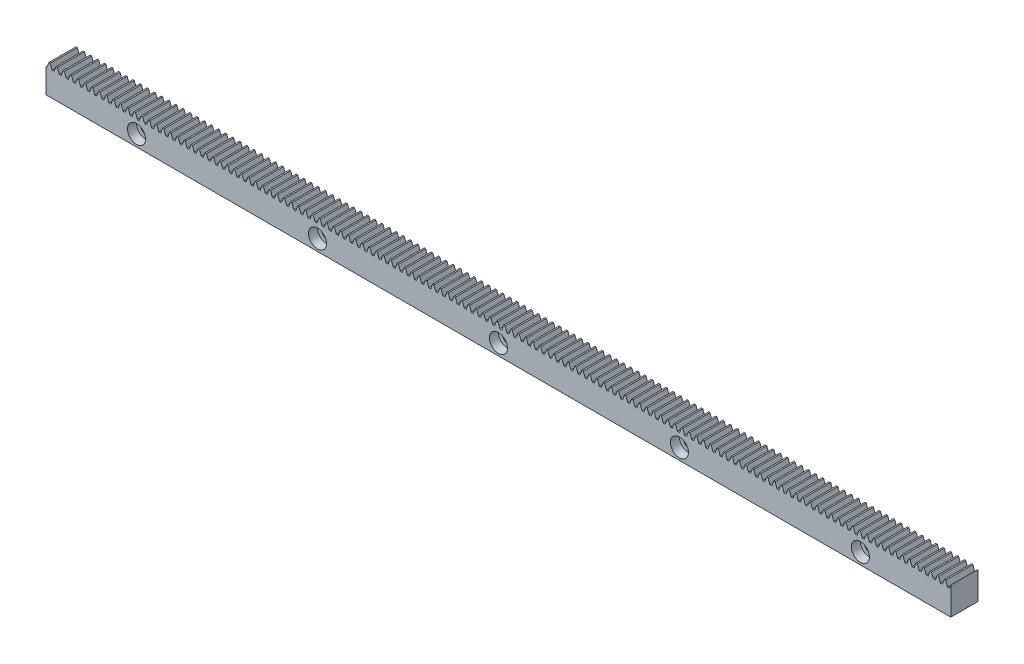
SolidWorks part; units mm, degrees
extrude "Blank" add sketch "BlankSke" against normal blind 12
sketch "BlankSke" plane through (0, 0, 0) normal (0, 0, 1) x (1, 0, 0)
  line L1 (0, 0) -> (400, 0)
  line L2 (0, 0) -> (0, 13)
  line L3 (0, 13) -> (400, 13)
  line L4 (400, 0) -> (400, 13)
  dimension "Length" = 400
  dimension "Blank_height" = 13
ref_plane "Plane1" through (0, 0, 0) normal (0, 0, 1) x (1, 0, 0)
ref_plane "Plane2" through (0, 0, 0) normal (0, 1, 0) x (1, 0, 0)
ref_plane "Plane3" through (0, 0, 0) normal (1, 0, 0) x (0, 0, -1)
sketch "HoldingSke" plane through (0, 0, 0) normal (0, 1, 0) x (1, 0, 0)
  line L0 (0, 0) -> (-0.766, -0.6428)
  line L1 (-15, 0) -> (100, 0) construction
  line L2 (0, 0) -> (-2.1039, 2.3779)
  line L3 (0, 0) -> (-11.863, 4.5341)
  line L4 (0, 0) -> (-5.4348, 6.7114)
  line L5 (0, 0) -> (-23.7986, -8.8762)
  line L6 (0, 0) -> (-10.5278, -7.1032)
  line L9 (-71.009, 38.7566) -> (304.8681, 175.5647)
  line L10 (-76.2, 3.3779) -> (-64.2, 3.3779)
  line L11 (0, 0) -> (-6.35, 0)
  line L12 (-76.2, 101.6) -> (-76.162, 101.6)
  line L13 (24.9733, 27.94) -> (52.9518, 28.4284)
  line L14 (24.9733, 27.94) -> (24.9743, 27.94)
  line L15 (24.9733, 27.94) -> (100.4006, 29.5858)
  circle A0 centre (0, 0) radius 19.05
  circle A1 centre (0, 0) radius 6
  circle A2 centre (0, 0) radius 12.7
  dimension "MPH" = 12
  dimension "Diameter" = 38.1
  dimension "Num_teeth" = 129
  dimension "Pitch" = 1
  dimension "Show_teeth" = 500
  dimension "Thickness" = 12.7
  dimension "Ap" = 20
  dimension "Pitch_height" = 12
  dimension "Width" = 6.35
  dimension "Backlash" = 0.038
  dimension "Addendum_fac" = 1
  dimension "Dedendum_fac" = 1.25
  dimension "Clearance_fac" = 0.25
  dimension "Dedendum_add" = 0.001
  dimension "Length" = 400
  dimension "Module" = 1
sketch "TooCutSkeIll" plane through (0, 0, 0) normal (0, 0, 1) x (1, 0, 0)
  line L0 (-1.2538, 12.9737) -> (-0.5045, 10.9152)
  line L1 (-0.2687, 10.75) -> (0.2687, 10.75)
  line L2 (0.5045, 10.9152) -> (1.2538, 12.9737)
  line L3 (400, 13) -> (0, 13) construction
  line L4 (0, 0) -> (0, 64.897) construction
  line L5 (-13.208, 12) -> (12.954, 12) construction
  line L6 (0, 0) -> (400, 0) construction
  line L7 (0.8994, 12) -> (0.8994, 48.7463) construction
  line L8 (-0.8994, 12) -> (-0.8994, 48.7463) construction
  line L9 (1.2914, 13) -> (1.2914, 13.0254)
  line L10 (-1.2914, 13) -> (-1.2914, 13.0254)
  line L11 (-1.2914, 13.0254) -> (1.2914, 13.0254)
  arc A0 (0.2687, 10.75) -> (0.5045, 10.9152) centre (0.2687, 11.001) ccw
  arc A1 (-0.5045, 10.9152) -> (-0.2687, 10.75) centre (-0.2687, 11.001) ccw
  arc A2 (1.2914, 13) -> (1.2538, 12.9737) centre (1.2914, 12.96) ccw
  arc A3 (-1.2538, 12.9737) -> (-1.2914, 13) centre (-1.2914, 12.96) ccw
  dimension "Pitch_height" = 12
  dimension "Addendum_plus" = 1.0254
  dimension "Pressure_angle" = 20
  dimension "Gap_width" = 1.7988
  dimension "Dedendum" = 1.25
extrude "ToothCutIll" [suppressed] cut sketch "TooCutSkeIll" against normal through all
sketch "TooCutSkeSim" plane through (0, 0, 0) normal (0, 0, 1) x (1, 0, 0)
  line L0 (0.4444, 10.75) -> (-0.4444, 10.75)
  line L1 (1.2726, 13.0254) -> (0.4444, 10.75)
  line L2 (0, 17.4625) -> (0, 53.467) construction
  line L3 (1.2726, 13.0254) -> (-1.2726, 13.0254)
  line L6 (-1.2726, 13.0254) -> (-0.4444, 10.75)
  line L9 (-0.8994, 12) -> (0.8994, 12) construction
  line L10 (0, 0) -> (400, 0) construction
  line L11 (0.8994, 12) -> (0.8994, 53.467) construction
  line L12 (-0.8994, 12) -> (-0.8994, 53.467) construction
  dimension "Pitch_height" = 12
  dimension "Addendum_plus" = 1.0254
  dimension "Pressure_angle" = 20
  dimension "Gap_width" = 1.7988
  dimension "Dedendum" = 1.25
extrude "ToothCutSim" cut sketch "TooCutSkeSim" against normal through all
pattern_linear "TeethCuts" count 128 spacing 3.1416 along (1, 0, 0) of "ToothCutIll", "ToothCutSim"
hole_wizard "M4 凹頭蓋螺釘的柱孔1" positions "3D草圖2" profile "草圖3" counterbore size "M4" standard "Ansi Metric" end condition through all
sketch3d "3D草圖2"
  line L0 (0, 0, 0) -> (400, 0, 0) construction
  line L1 (0, 10.75, 0) -> (0, 0, 0) construction
  point P0 (40, 5, 0)
  dimension "D1" = 5
  dimension "D2" = 40
sketch "草圖3" plane through (40, 5, 0) normal (1, 0, 0) x (0, -1, 0)
  line L0 (0, 0) -> (0, 12)
  line L1 (0, 12) -> (2.15, 12)
  line L3 (2.15, 12) -> (2.15, 4)
  line L4 (2.15, 4) -> (4, 4)
  line L5 (4, 4) -> (4, 0)
  line L7 (4, 0) -> (0, 0)
  line L11 (0, -6.35) -> (0, 107.95) construction
  dimension "貫穿孔直徑" = 4.3
  dimension "貫穿孔深度" = 12
  dimension "柱孔直徑" = 8
  dimension "柱孔深度" = 4
pattern_linear "直線複製排列1" count 5 spacing 80 along (1, 0, 0) of "M4 凹頭蓋螺釘的柱孔1"
equation "' \"Module@HoldingSke\" = 6.35"
equation "' \"Num_teeth@HoldingSke\" = 12"
equation "' \"Ap@HoldingSke\" =  20"
equation "' \"Ap@HoldingSke\" = 20"
equation "' \"Width@HoldingSke\" = 0.25 * 25.4"
equation "' \"Show_teeth@HoldingSke\" = 500"
equation "' \"Backlash@HoldingSke\" = 0.009 * 25.4"
equation "' \"Addendum_fac@HoldingSke\" = 1.0"
equation "' \"Dedendum_fac@HoldingSke\" = 1.25"
equation "' \"Dedendum_add@HoldingSke\" = 0.00005 * 25.4"
equation "' \"Clearance_fac@HoldingSke\" = 0.25"
equation "' \"Pitch_height@HoldingSke\" = 1 * 25.4"
equation "' \"Length@HoldingSke\" = 4.71 * 25.4"
equation "\"Pitch@HoldingSke\" = 1 / \"Module@HoldingSke\""
equation "\"MPH@HoldingSke\" = \"Dedendum_fac@HoldingSke\" / \"Pitch@HoldingSke\" + 2 * \"Dedendum_add@HoldingSke\" + 0.002 * 25.4"
equation "\"MPH@HoldingSke\" = ((sgn( \"MPH@HoldingSke\" - \"Pitch_height@HoldingSke\")+1)*( \"MPH@HoldingSke\" - \"Pitch_height@HoldingSke\"))/2 + \"Pitch_height@HoldingSke\""
equation "\"Blank_height@BlankSke\" = \"Pitch_height@HoldingSke\" + \"Addendum_fac@HoldingSke\"  / \"Pitch@HoldingSke\" "
equation "\"Length@BlankSke\" =  \"Length@HoldingSke\""
equation "\"Pressure_angle@TooCutSkeIll\" = \"Ap@HoldingSke\""
equation "\"Addendum_plus@TooCutSkeIll\" =  \"Addendum_fac@HoldingSke\"  / \"Pitch@HoldingSke\" + 0.001 *25.4"
equation "\"Dedendum@TooCutSkeIll\" = \"Dedendum_fac@HoldingSke\"  / \"Pitch@HoldingSke\""
equation "\"Pitch_height@TooCutSkeIll\" =  \"MPH@HoldingSke\""
equation "\"Gap_width@TooCutSkeIll\" = 3.14159265 / 2 / \"Pitch@HoldingSke\" + 6 * \"Backlash@HoldingSke\""
equation "\"Pressure_angle@TooCutSkeSim\" = \"Ap@HoldingSke\""
equation "\"Addendum_plus@TooCutSkeSim\" =  \"Addendum_fac@HoldingSke\"  / \"Pitch@HoldingSke\" + 0.001 * 25.4"
equation "\"Dedendum@TooCutSkeSim\" = \"Dedendum_fac@HoldingSke\"  / \"Pitch@HoldingSke\""
equation "\"Pitch_height@TooCutSkeSim\" =  \"MPH@HoldingSke\""
equation "\"Gap_width@TooCutSkeSim\" = 3.14159265 / 2 / \"Pitch@HoldingSke\" + 6 * \"Backlash@HoldingSke\""
equation "\"Root_fillet@TooCutSkeIll\" = \"Clearance_fac@HoldingSke\" / \"Pitch@HoldingSke\" + \"Dedendum_add@HoldingSke\""
equation "\"Break_rad@TooCutSkeIll\" = 0.02 / \"Pitch@HoldingSke\" * 2"
equation "\"Linear_pitch@TeethCuts\" = 3.14159265 / \"Pitch@HoldingSke\""
equation "\"Num_teeth@HoldingSke\" = int( ( \"Length@HoldingSke\" + 0 ) / (3.14159265 / \"Pitch@HoldingSke\")) + 0.9999  + 1"
equation " \"Num_teeth@TeethCuts\" = int( \"Show_teeth@HoldingSke\" ) + 1"
equation " \"Num_teeth@TeethCuts\" = ((sgn( \"Num_teeth@TeethCuts\" - \"Num_teeth@HoldingSke\" )-1)*( \"Num_teeth@TeethCuts\" - \"Num_teeth@HoldingSke\" ))/-2+ \"Num_teeth@HoldingSke\""
equation " \"Num_teeth@TeethCuts\" = ((sgn( \"Num_teeth@TeethCuts\" - 2.0)+1)*( \"Num_teeth@TeethCuts\" - 2.0))/2 +2.0"
